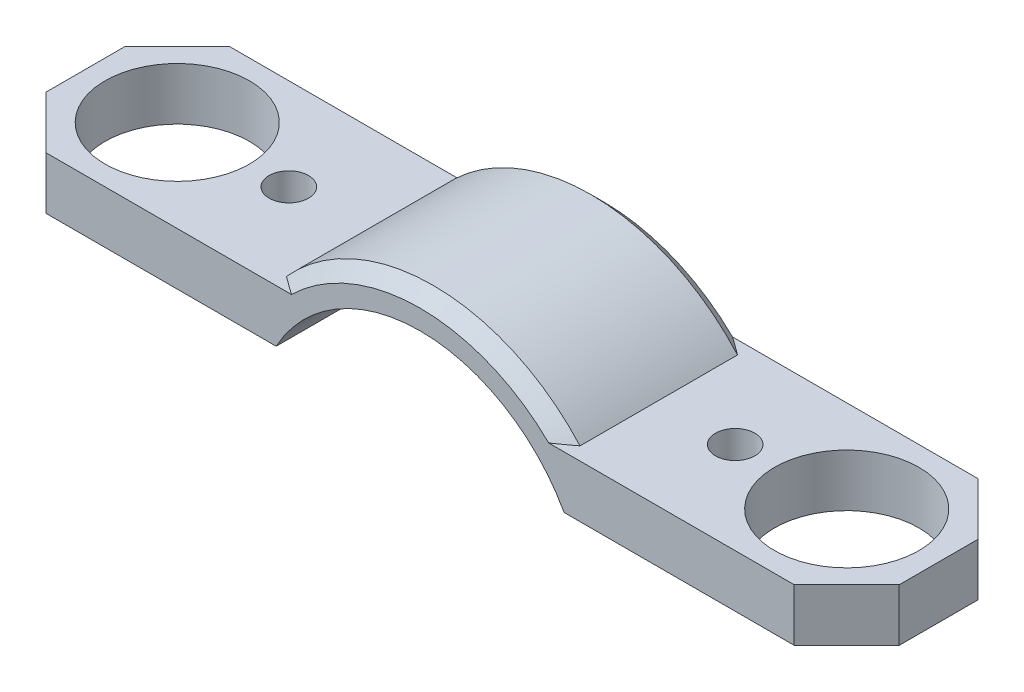
SolidWorks part; units mm, degrees
ref_plane "Plan de face" through (0, 0, 0) normal (0, 0, 1) x (1, 0, 0)
ref_plane "Plan de dessus" through (0, 0, 0) normal (0, 1, 0) x (1, 0, 0)
ref_plane "Plan de droite" through (0, 0, 0) normal (1, 0, 0) x (0, 0, -1)
sketch "Esquisse2" plane through (0, 0, 0) normal (0, 1, 0) x (1, 0, 0)
  line L1 (-35.8261, 4.6472) -> (29.1739, 4.6472)
  line L2 (-35.8261, 4.6472) -> (-35.8261, -9.3528)
  line L3 (-35.8261, -9.3528) -> (29.1739, -9.3528)
  line L4 (29.1739, 4.6472) -> (29.1739, -9.3528)
  dimension "D1" = 65
  dimension "D6" = 14
extrude "Boss.-Extru.1" add sketch "Esquisse2" against normal blind 4
sketch "Esquisse3" plane through (0, -4, 0) normal (0, -1, 0) x (1, 0, 0)
  line L0 (-35.8261, 2.3528) -> (29.1739, 2.3528) construction
  line L1 (-35.8261, -4.6472) -> (-35.8261, 9.3528) construction
  line L2 (29.1739, 9.3528) -> (29.1739, -4.6472) construction
  circle A0 centre (-28.8261, 2.3528) radius 5.5
  circle A1 centre (22.1739, 2.3528) radius 5.5
  circle A2 centre (-20.3261, 2.3528) radius 1.5
  circle A3 centre (13.6739, 2.3528) radius 1.5
  dimension "D1" = 11
  dimension "D2" = 11
  dimension "D5" = 3
  dimension "D6" = 3
  dimension "D3" = 7
  dimension "D4" = 7
  dimension "D7" = 8.5
  dimension "D8" = 8.5
extrude "Enlèv. mat.-Extru.1" cut sketch "Esquisse3" against normal blind 4
sketch "Esquisse5" plane through (0, 0, -4.6472) normal (0, 0, -1) x (-1, 0, 0)
  line L0 (-29.1739, 0) -> (-29.1739, -26.7463) construction
  line L1 (35.8261, 0) -> (35.8261, -25.6795) construction
  line L2 (-29.1739, -10) -> (35.8261, -10) construction
  line L3 (-29.1739, 0) -> (35.8261, 0) construction
  line L4 (-10.4216, -4) -> (17.0738, -4)
  line L5 (-29.1739, -4) -> (35.8261, -4) construction
  arc A0 (17.0738, -4) -> (-10.4216, -4) centre (3.3261, -10) ccw
  dimension "D2" = 30
  dimension "D1" = 10
extrude "Boss.-Extru.3" add sketch "Esquisse5" against normal blind 14
sketch "Esquisse7" plane through (0, 0, -4.6472) normal (0, 0, -1) x (-1, 0, 0)
  circle A0 centre (3.3261, -10) radius 12.5
  dimension "D1" = 25
extrude "Enlèv. mat.-Extru.4" cut sketch "Esquisse7" against normal through all
chamfer "Chanfrein1" distance 4 angle 45 4 edges at (-35.8261, -2, -4.6472) (-35.8261, -2, 9.3528) (29.1739, -2, -4.6472) (29.1739, -2, 9.3528)
chamfer "Chanfrein2" distance 1 angle 45 2 edges at (-3.3261, 5, 9.3528) (-3.3261, 5, -4.6472)
